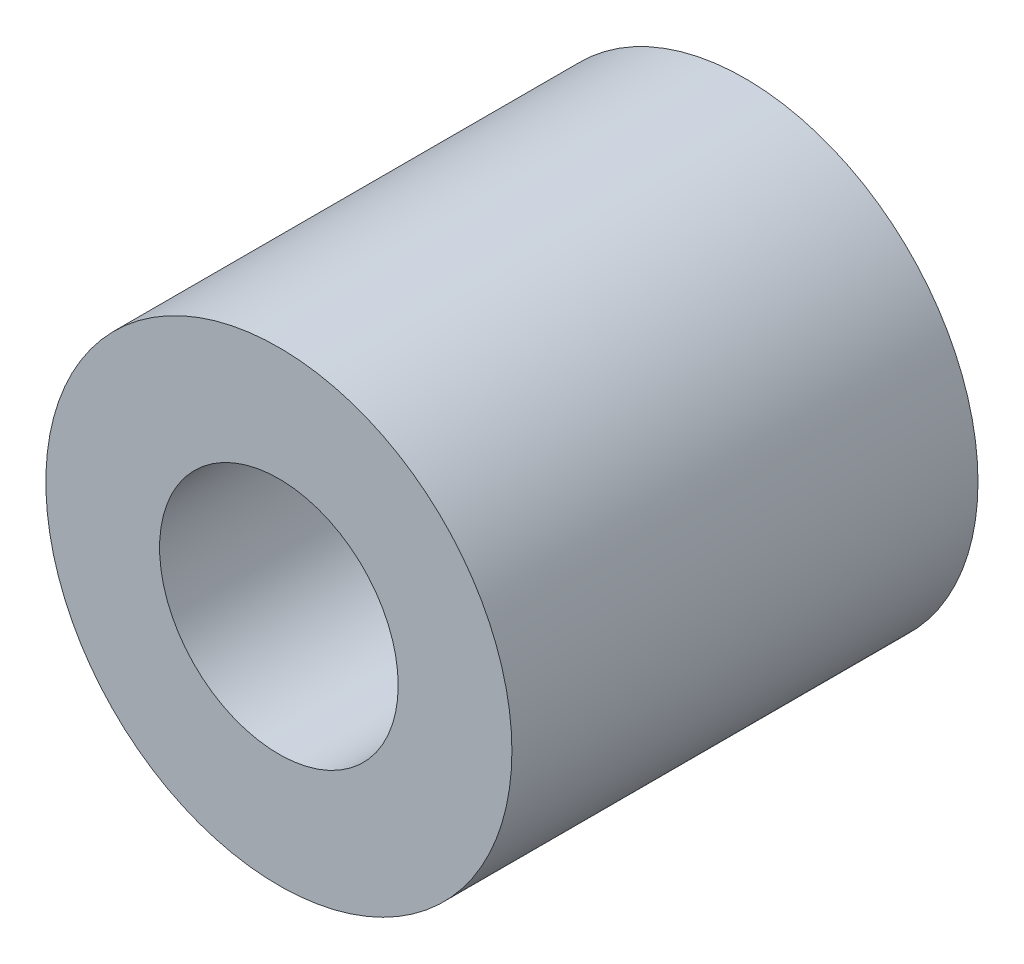
SolidWorks part; units mm, degrees
material "Nylon 6/6"
ref_plane "Front" through (0, 0, 0) normal (0, 0, 1) x (1, 0, 0)
ref_plane "Top" through (0, 0, 0) normal (0, 1, 0) x (1, 0, 0)
ref_plane "Right" through (0, 0, 0) normal (1, 0, 0) x (0, 0, -1)
sketch "Sketch1" plane through (0, 0, 0) normal (0, 0, 1) x (1, 0, 0)
  circle A0 centre (0, 0) radius 1.5875
  circle A1 centre (0, 0) radius 0.8128
  dimension "ID" = 1.6256
  dimension "OD" = 3.175
extrude "Boss-Extrude1" add sketch "Sketch1" along normal mid plane 3.175
